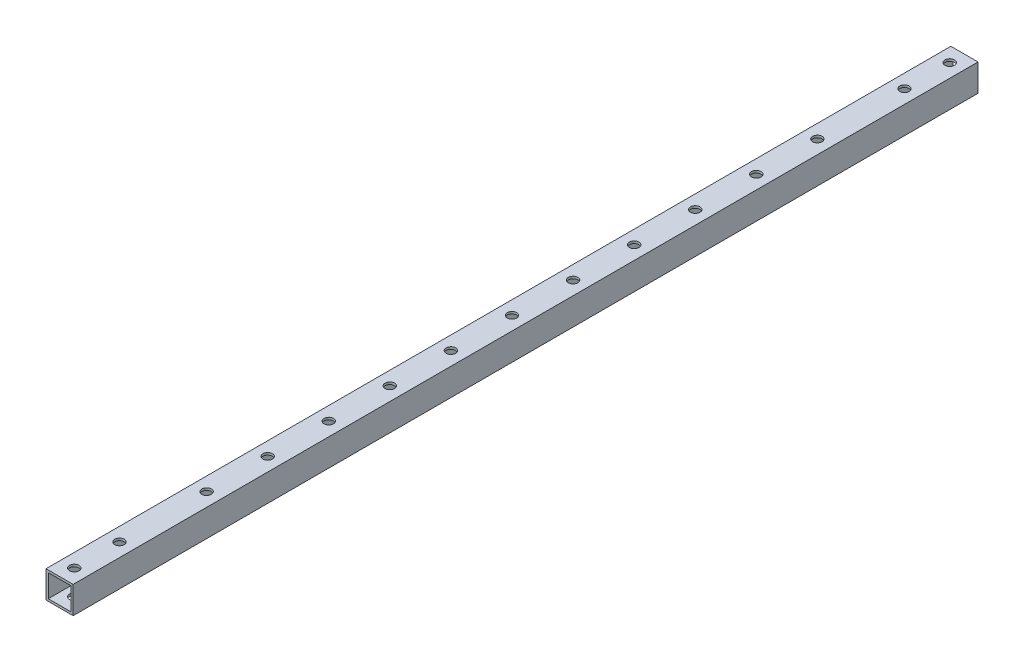
SolidWorks part; units mm, degrees
ref_plane "前视基准面" through (0, 0, 0) normal (0, 0, 1) x (1, 0, 0)
ref_plane "上视基准面" through (0, 0, 0) normal (0, 1, 0) x (1, 0, 0)
ref_plane "右视基准面" through (0, 0, 0) normal (1, 0, 0) x (0, 0, -1)
other "Configuration Table"
sketch "草图1" plane through (0, 0, 0) normal (0, 0, 1) x (1, 0, 0)
  line L0 (-5, 5) -> (-5, -5)
  line L1 (-6, 6) -> (-6, -6)
  line L2 (-6, -6) -> (6, -6)
  line L3 (6, -6) -> (6, 6)
  line L4 (6, 6) -> (-6, 6)
  line L5 (-5, -5) -> (5, -5)
  line L6 (5, -5) -> (5, 5)
  line L7 (5, 5) -> (-5, 5)
  circle A0 centre (0, 0) radius 6 construction
  dimension "D1" = 12
  dimension "D2" = 1
extrude "凸台-拉伸1" add sketch "草图1" along normal blind 400
sketch "草图2" plane through (0, 6, 0) normal (0, 1, 0) x (1, 0, 0)
  line L0 (6, -200) -> (-6, -200) construction
  line L1 (6, -400) -> (6, 0) construction
  line L2 (-6, -400) -> (-6, 0) construction
  line L3 (0, 0) -> (0, -400) construction
  line L4 (6, -400) -> (-6, -400) construction
  circle A0 centre (0, -200) radius 2.1
  circle A1 centre (0, -227) radius 2.1
  circle A2 centre (0, -254) radius 2.1
  circle A3 centre (0, -281) radius 2.1
  circle A4 centre (0, -308) radius 2.1
  circle A5 centre (0, -335) radius 2.1
  circle A6 centre (0, -173) radius 2.1
  circle A7 centre (0, -146) radius 2.1
  circle A8 centre (0, -119) radius 2.1
  circle A9 centre (0, -92) radius 2.1
  circle A10 centre (0, -65) radius 2.1
  dimension "D1" = 4.2
  dimension "D2" = 6
  dimension "D3" = 6
extrude "切除-拉伸1" cut sketch "草图2" against normal blind 500
sketch "草图3" plane through (0, 6, 0) normal (0, 1, 0) x (1, 0, 0)
  line L0 (0, 0) -> (0, -400) construction
  line L1 (6, -400) -> (-6, -400) construction
  line L2 (-6, -200) -> (6, -200) construction
  line L3 (-6, -400) -> (-6, 0) construction
  line L4 (6, -400) -> (6, 0) construction
  line L5 (6, 0) -> (-6, 0) construction
  circle A0 centre (0, -6.5) radius 2.1
  circle A1 centre (0, -26.5) radius 2.1
  circle A2 centre (0, -373.5) radius 2.1
  circle A3 centre (0, -393.5) radius 2.1
  dimension "D1" = 4.2
  dimension "D2" = 6.5
  dimension "D3" = 20
extrude "切除-拉伸2" cut sketch "草图3" against normal blind 102
